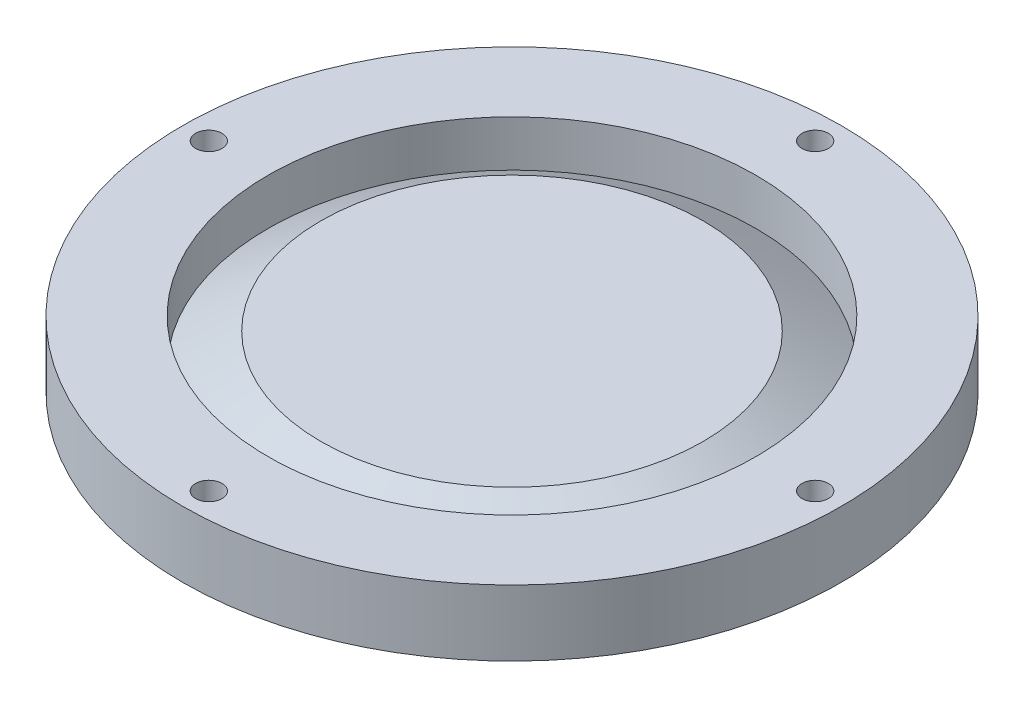
SolidWorks part; units mm, degrees
ref_plane "前视基准面" through (0, 0, 0) normal (0, 0, 1) x (1, 0, 0)
ref_plane "上视基准面" through (0, 0, 0) normal (0, 1, 0) x (1, 0, 0)
ref_plane "右视基准面" through (0, 0, 0) normal (1, 0, 0) x (0, 0, -1)
other "Configuration Table"
sketch "草图1" plane through (0, 0, 0) normal (0, 1, 0) x (1, 0, 0)
  circle A0 centre (0, 0) radius 25
  dimension "D1" = 50
extrude "凸台-拉伸1" add sketch "草图1" along normal blind 5
sketch "草图4" plane through (0, 0, 0) normal (0, 0, 1) x (1, 0, 0)
  line L0 (0, 0) -> (0, 5) construction
  line L1 (25, 5) -> (-25, 5) construction
  line L2 (14.5, 5) -> (14.5, 4)
  line L3 (14.5, 4) -> (18.5, 1.5)
  line L4 (18.5, 1.5) -> (18.5, 5)
  line L6 (18.5, 5) -> (14.5, 5)
  line L7 (14.5, 4) -> (0, 4)
  line L9 (0, 4) -> (0, 5)
  line L10 (0, 5) -> (14.5, 5)
  dimension "D1" = 14.5
  dimension "D2" = 18.5
  dimension "D3" = 2.5
  dimension "D4" = 1
revolve "切除-旋转1" cut sketch "草图4" angle 360 about L0
sketch "草图5" plane through (0, 5, 0) normal (0, 1, 0) x (1, 0, 0)
  line L0 (0, 0) -> (0, 23) construction
  circle A0 centre (0, 23) radius 1
  circle A1 centre (23, 0) radius 1
  circle A2 centre (0, -23) radius 1
  circle A3 centre (-23, 0) radius 1
  point P13 (0, 0)
  dimension "D1" = 2
  dimension "D2" = 23
  dimension "D3" = 4
extrude "切除-拉伸3" cut sketch "草图5" against normal through all
